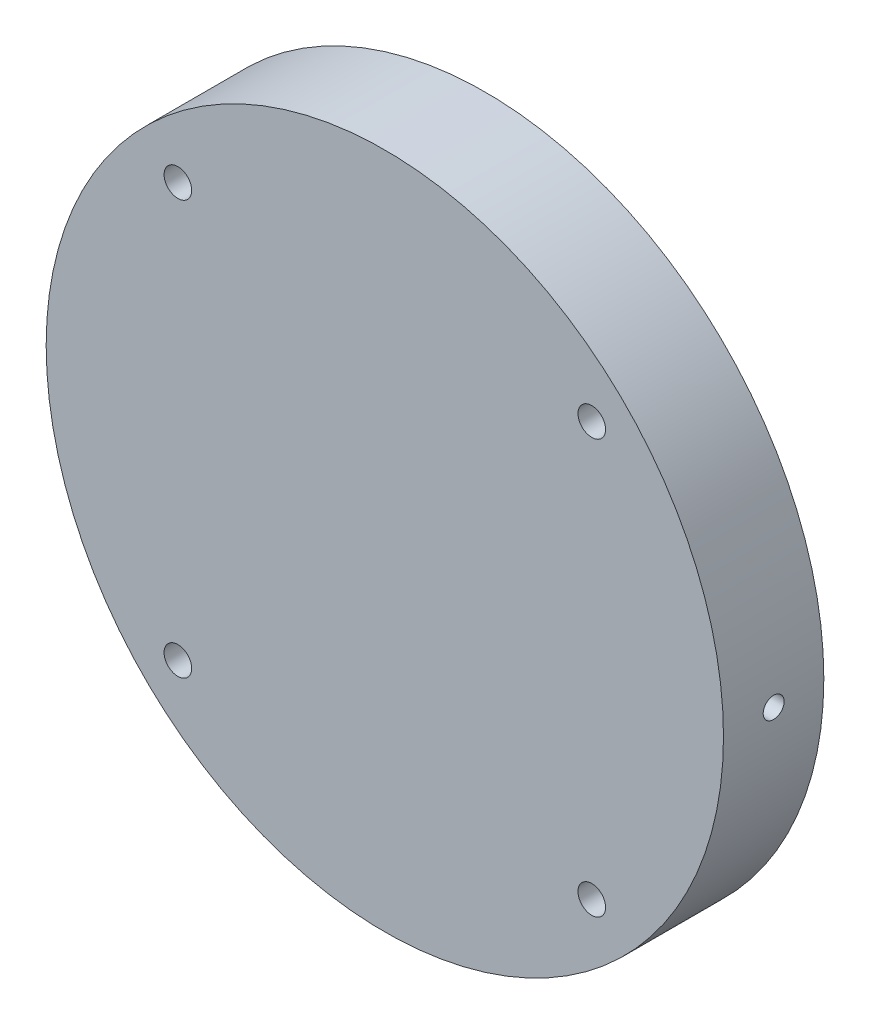
SolidWorks part; units mm, degrees
material "1.4021 (X20Cr13)"
ref_plane "Front Plane" through (0, 0, 0) normal (0, 0, 1) x (1, 0, 0)
ref_plane "Top Plane" through (0, 0, 0) normal (0, 1, 0) x (1, 0, 0)
ref_plane "Right Plane" through (0, 0, 0) normal (1, 0, 0) x (0, 0, -1)
ref_plane "Plane1" through (0, 0, 0) normal (0, -1, 0) x (1, 0, 0)
sketch "Sketch1" plane through (0, 0, 0) normal (0, -1, 0) x (1, 0, 0)
  line L0 (40.5, 12) -> (0, 12)
  line L1 (0, 12) -> (0, 0)
  line L2 (0, 0) -> (40.5, 0)
  line L3 (40.5, 0) -> (40.5, 12)
  line L4 (0, 12) -> (0, 0) construction
  dimension "D1" = 40.5
  dimension "D2" = 12
  dimension "D3" = 40.5
  dimension "D4" = 12
revolve "Revolve1" add sketch "Sketch1" angle 360 about L4
hole_wizard "Ø2.5 (2.5) Diameter Hole1" positions "3DSketch1" profile "Sketch2" hole size "Ø2.5" standard "ANSI Metric"
sketch3d "3DSketch1"
  point P0 (40.5, 0, 6)
sketch "Sketch2" plane through (40.5, 0, 6) normal (0, 1, 0) x (0, 0, -1)
  line L0 (0, 0) -> (0, 10)
  line L1 (0, 10) -> (1.25, 10)
  line L2 (1.25, 10) -> (1.25, 0)
  line L5 (1.25, 0) -> (0, 0)
  line L10 (0, 10) -> (-1.25, 10) construction
  line L11 (0, -6.35) -> (0, 107.95) construction
  dimension "Hole Dia." = 2.5
  dimension "Hole Depth" = 10
  dimension "Drill Angle" = 180
hole_wizard "Ø3.3 (3.3) Diameter Hole1" positions "Sketch4" profile "Sketch3" hole size "Ø3.3" standard "ANSI Metric"
sketch "Sketch4" plane through (0, 0, 12) normal (0, 0, 1) x (1, 0, 0)
  point P0 (24.7487, 24.7487)
  point P1 (-24.7487, 24.7487)
  point P2 (24.7487, -24.7487)
  point P3 (-24.7487, -24.7487)
  dimension "D1" = 24.7487
  dimension "D2" = 24.7487
  dimension "D3" = 24.7487
  dimension "D4" = 24.7487
  dimension "D5" = 24.7487
  dimension "D6" = 24.7487
  dimension "D7" = 24.7487
  dimension "D8" = 24.7487
sketch "Sketch3" plane through (24.7487, 24.7487, 12) normal (1, 0, 0) x (0, -1, 0)
  line L0 (0, 0) -> (0, 8)
  line L1 (0, 8) -> (1.65, 8)
  line L2 (1.65, 8) -> (1.65, 0)
  line L5 (1.65, 0) -> (0, 0)
  line L10 (0, 8) -> (-1.65, 8) construction
  line L11 (0, -6.35) -> (0, 107.95) construction
  dimension "Hole Dia." = 3.3
  dimension "Hole Depth" = 8
  dimension "Drill Angle" = 180
